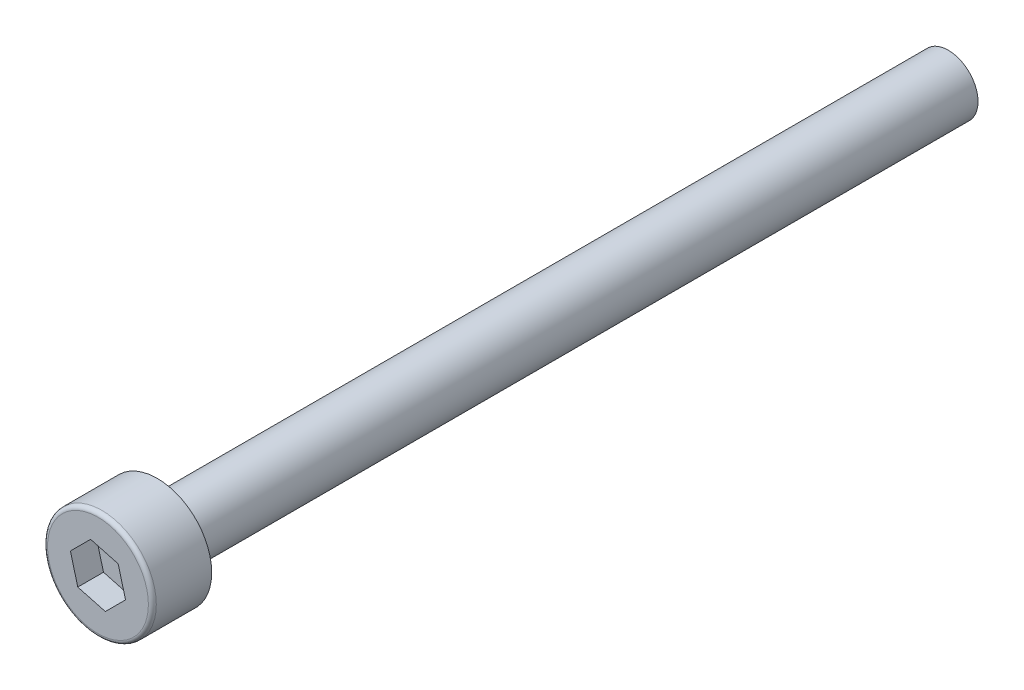
SolidWorks part; units mm, degrees
ref_plane "前视基准面" through (0, 0, 0) normal (0, 0, 1) x (1, 0, 0)
ref_plane "上视基准面" through (0, 0, 0) normal (0, 1, 0) x (1, 0, 0)
ref_plane "右视基准面" through (0, 0, 0) normal (1, 0, 0) x (0, 0, -1)
sketch "草图1" plane through (0, 0, 0) normal (0, 0, 1) x (1, 0, 0)
  circle A0 centre (0, 0) radius 2.75
  dimension "D1" = 5.5
extrude "凸台-拉伸1" add sketch "草图1" along normal blind 3
sketch "草图2" plane through (0, 0, 3) normal (0, 0, 1) x (1, 0, 0)
  line L1 (-1.0206, -1.0206) -> (0.3736, -1.3942)
  line L2 (0.3736, -1.3942) -> (1.3942, -0.3736)
  line L3 (1.3942, -0.3736) -> (1.0206, 1.0206)
  line L4 (1.0206, 1.0206) -> (-0.3736, 1.3942)
  line L5 (-0.3736, 1.3942) -> (-1.3942, 0.3736)
  line L6 (-1.3942, 0.3736) -> (-1.0206, -1.0206)
  circle A0 centre (0, 0) radius 1.25 construction
  dimension "D1" = 2.5
extrude "切除-拉伸1" cut sketch "草图2" against normal blind 1.3
sketch "草图3" plane through (0, 0, 0) normal (0, 0, -1) x (-1, 0, 0)
  circle A0 centre (0, 0) radius 1.5
  dimension "D1" = 3
extrude "凸台-拉伸2" add sketch "草图3" along normal blind 40
fillet "圆角1" radius 0.2 1 edges at (2.75, 0, 3)
